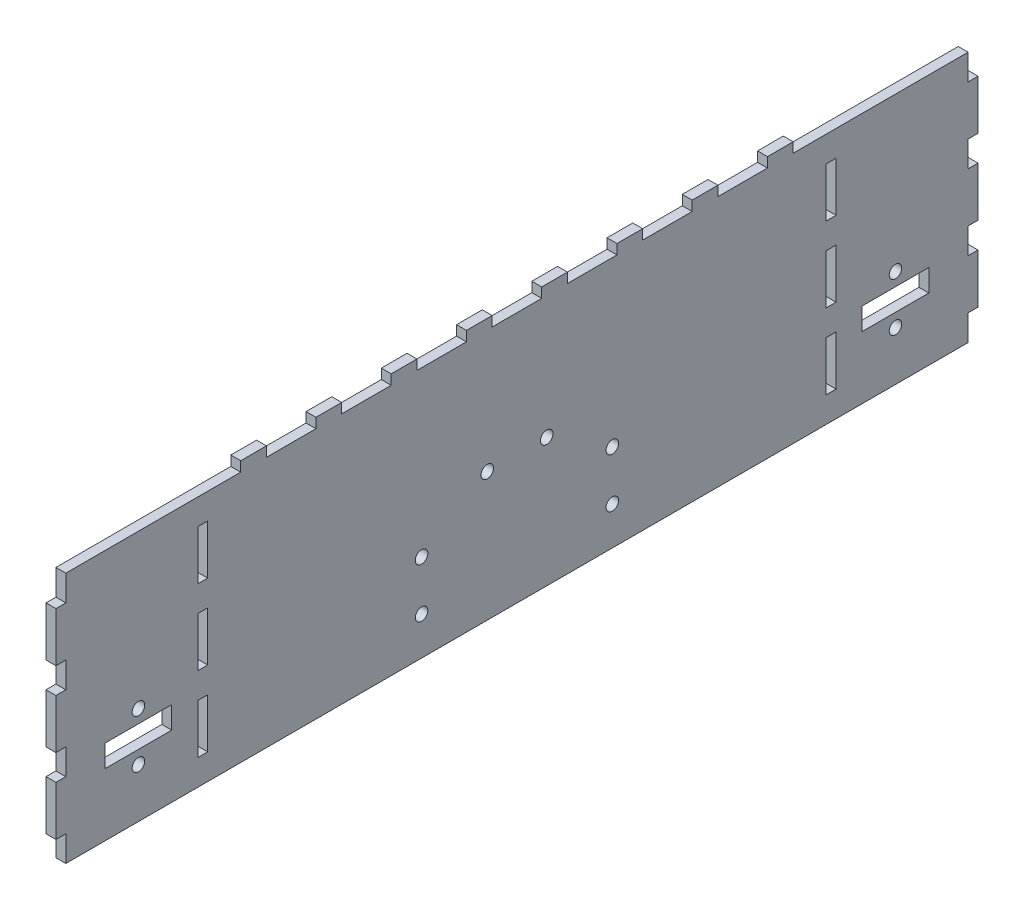
SolidWorks part; units mm, degrees
material "ENPH 253 Hardboard"
ref_plane "Front Plane" through (0, 0, 0) normal (0, 0, 1) x (1, 0, 0)
ref_plane "Top Plane" through (0, 0, 0) normal (0, 1, 0) x (1, 0, 0)
ref_plane "Right Plane" through (0, 0, 0) normal (1, 0, 0) x (0, 0, -1)
sketch "Sketch1" plane through (0, 0, 0) normal (1, 0, 0) x (0, 0, -1)
  line L1 (-139.7, 38.1) -> (139.7, 38.1)
  line L2 (-139.7, 38.1) -> (-139.7, -38.1)
  line L3 (-139.7, -38.1) -> (139.7, -38.1)
  line L4 (139.7, 38.1) -> (139.7, -38.1)
  line L5 (-139.7, 38.1) -> (139.7, -38.1) construction
  line L6 (-139.7, -38.1) -> (139.7, 38.1) construction
  point P0 (0, 0)
  dimension "D1" = 279.4
  dimension "D2" = 76.2
extrude "Boss-Extrude1" add sketch "Sketch1" against normal blind 3 contours L2 L3 L4 L1
sketch "Sketch3" plane through (-3, 0, 0) normal (-1, 0, 0) x (0, 0, 1)
  line L9 (-139.7, 38.1) -> (-136.7, 38.1)
  line L10 (-139.7, 38.1) -> (-139.7, 30.3)
  line L11 (-139.7, 30.3) -> (-136.7, 30.3)
  line L12 (-136.7, 38.1) -> (-136.7, 30.3)
  dimension "D9" = 7.8
  dimension "D10" = 3
extrude "Cut-Extrude1" cut sketch "Sketch3" against normal through all
pattern_linear "LPattern1" count 4 spacing 22.8 along (0, -1, 0) of "Cut-Extrude1"
mirror "Mirror1" about plane through (0, 0, 0) normal (0, 0, 1) of "LPattern1", "Cut-Extrude1"
sketch "Sketch4" plane through (0, 0, 0) normal (1, 0, 0) x (0, 0, -1)
  line L1 (-96.7, 30.3) -> (-93.7, 30.3)
  line L2 (-96.7, 30.3) -> (-96.7, 15.3)
  line L3 (-96.7, 15.3) -> (-93.7, 15.3)
  line L4 (-93.7, 30.3) -> (-93.7, 15.3)
  line L5 (-136.7, 38.1) -> (136.7, 38.1) construction
  line L6 (-136.7, 30.3) -> (-136.7, 38.1) construction
  dimension "D1" = 40
  dimension "D2" = 3
  dimension "D3" = 7.8
  dimension "D4" = 15
extrude "Cut-Extrude2" cut sketch "Sketch4" against normal blind 10
pattern_linear "LPattern2" count 3 spacing 22.8 along (0, -1, 0) of "Cut-Extrude2"
mirror "Mirror2" about plane through (0, 0, 0) normal (0, 0, 1) of "LPattern2", "Cut-Extrude2"
sketch "Sketch5" plane through (0, 38.1, 0) normal (0, 1, 0) x (1, 0, 0)
  line L0 (-3, -136.7) -> (-3, 136.7) construction
  line L1 (-3, -75.9) -> (0, -75.9)
  line L2 (-3, -75.9) -> (-3, -83.7)
  line L3 (-3, -83.7) -> (0, -83.7)
  line L4 (0, -75.9) -> (0, -83.7)
  line L5 (0, -136.7) -> (-3, -136.7) construction
  dimension "D1" = 53
  dimension "D2" = 7.8
  dimension "D3" = 3
extrude "Boss-Extrude2" add sketch "Sketch5" along normal blind 3
pattern_linear "LPattern3" count 8 spacing 22.8 along (0, 0, -1) of "Boss-Extrude2"
hole_wizard "#6 Clearance Hole1" positions "Sketch6" profile "Sketch7" hole size "#6" standard "ANSI Inch" end condition up to next
sketch "Sketch6" plane through (-3, 0, 0) normal (-1, 0, 0) x (0, 0, 1)
  point P0 (-28.9, -11.55)
  point P3 (-28.9, -26.55)
  point P6 (28.9, -26.55)
  point P9 (28.9, -11.55)
sketch "Sketch7" plane through (-3, -11.55, -28.9) normal (0, 1, 0) x (0, 0, 1)
  line L0 (0, 0) -> (0, 3)
  line L1 (0, 3) -> (1.8986, 3)
  line L2 (1.8986, 3) -> (1.8986, 0)
  line L5 (1.8986, 0) -> (0, 0)
  line L11 (0, -6.35) -> (0, 107.95) construction
  dimension "Thru Hole Dia." = 3.7973
  dimension "Thru Hole Depth" = 3
hole_wizard "#6 Clearance Hole2" positions "Sketch8" profile "Sketch9" hole size "#6" standard "ANSI Inch" end condition through all
sketch "Sketch8" plane through (0, 0, 0) normal (1, 0, 0) x (0, 0, -1)
  point P0 (-9, 0.9)
  point P3 (9, 0.9)
sketch "Sketch9" plane through (0, 0.9, 9) normal (0, 1, 0) x (0, 0, -1)
  line L0 (0, 0) -> (0, 3)
  line L1 (0, 3) -> (1.8986, 3)
  line L2 (1.8986, 3) -> (1.8986, 0)
  line L5 (1.8986, 0) -> (0, 0)
  line L11 (0, -6.35) -> (0, 107.95) construction
  dimension "Thru Hole Dia." = 3.7973
  dimension "Thru Hole Depth" = 3
sketch "Sketch10" plane through (-3, 0, 0) normal (-1, 0, 0) x (0, 0, 1)
  line L0 (136.7, -38.1) -> (-136.7, -38.1) construction
  line L5 (124.7, -19.05) -> (104.7, -19.05) construction
  line L6 (124.7, -19.05) -> (124.7, -12.55) construction
  line L7 (124.7, -12.55) -> (104.7, -12.55) construction
  line L8 (104.7, -19.05) -> (104.7, -12.55) construction
  line L9 (139.7, -15.3) -> (139.7, -30.3) construction
  line L10 (124.8, -19.15) -> (124.8, -12.45)
  line L11 (124.8, -12.45) -> (104.6, -12.45)
  line L12 (104.6, -19.15) -> (104.6, -12.45)
  line L13 (124.8, -19.15) -> (104.6, -19.15)
  line L14 (0, 38.1) -> (0, -39.0089) construction
  line L15 (7.5, 38.1) -> (-7.5, 38.1) construction
  line L16 (-124.8, -19.15) -> (-104.6, -19.15)
  line L17 (-104.6, -19.15) -> (-104.6, -12.45)
  line L18 (-124.8, -12.45) -> (-104.6, -12.45)
  line L19 (-124.8, -19.15) -> (-124.8, -12.45)
  dimension "D1" = 19.05
  dimension "D2" = 15
  dimension "D3" = 20
  dimension "D4" = 6.5
  dimension "D5" = 0.1
extrude "Cut-Extrude3" cut sketch "Sketch10" against normal up to next
hole_wizard "#6 Clearance Hole3" positions "Sketch11" profile "Sketch12" hole size "#6" standard "ANSI Inch" end condition through all
sketch "Sketch11" plane through (-3, 0, 0) normal (-1, 0, 0) x (0, 0, 1)
  line L0 (-124.8, -15.8) -> (-104.6, -15.8) construction
  line L1 (-124.8, -12.45) -> (-124.8, -19.15) construction
  line L2 (-104.6, -19.15) -> (-104.6, -12.45) construction
  line L4 (0, 0) -> (0, -38.1) construction
  line L5 (136.7, -38.1) -> (-136.7, -38.1) construction
  line L7 (-104.6, -12.45) -> (-124.8, -12.45) construction
  point P0 (-114.7, -8.45)
  point P18 (-114.7, -15.8)
  point P21 (-114.7, -23.15)
  point P23 (114.7, -23.15)
  point P24 (114.7, -8.45)
  dimension "D1" = 4
sketch "Sketch12" plane through (-3, -8.45, -114.7) normal (0, 1, 0) x (0, 0, 1)
  line L0 (0, 0) -> (0, 3)
  line L1 (0, 3) -> (1.8986, 3)
  line L2 (1.8986, 3) -> (1.8986, 0)
  line L5 (1.8986, 0) -> (0, 0)
  line L11 (0, -6.35) -> (0, 107.95) construction
  dimension "Thru Hole Dia." = 3.7973
  dimension "Thru Hole Depth" = 3
